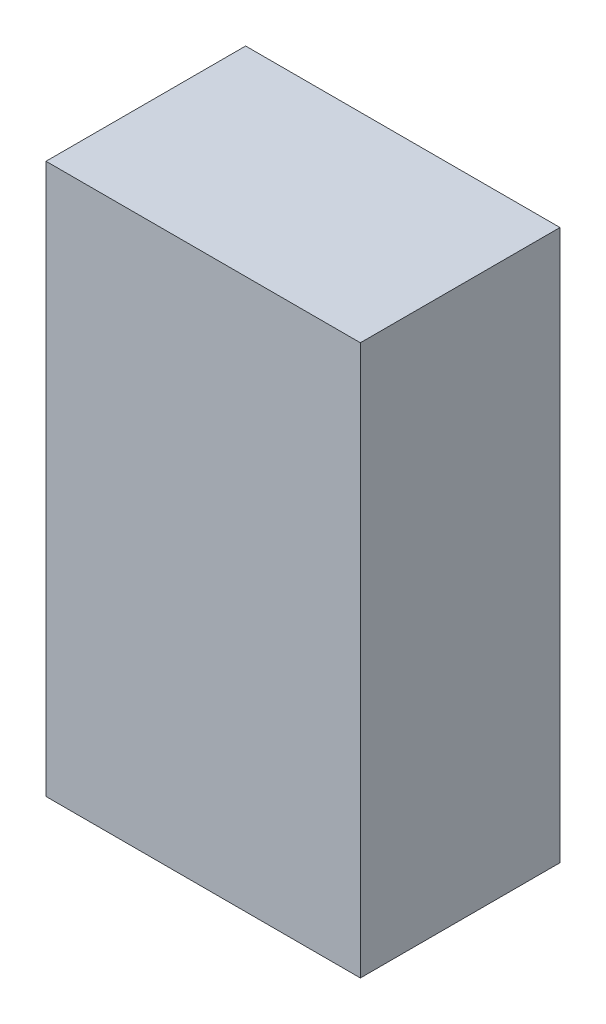
SolidWorks part; units mm, degrees
material "Custom Plastic"
ref_plane "Front Plane" through (0, 0, 0) normal (0, 0, 1) x (1, 0, 0)
ref_plane "Top Plane" through (0, 0, 0) normal (0, 1, 0) x (1, 0, 0)
ref_plane "Right Plane" through (0, 0, 0) normal (1, 0, 0) x (0, 0, -1)
sketch "Sketch1" plane through (0, 0, 0) normal (0, 0, 1) x (1, 0, 0)
  line L1 (0, 0) -> (20, 0)
  line L2 (0, 0) -> (0, -35)
  line L3 (0, -35) -> (20, -35)
  line L4 (20, 0) -> (20, -35)
  dimension "D1" = 35
  dimension "D2" = 20
extrude "Boss-Extrude1" add sketch "Sketch1" along normal blind 12.7
